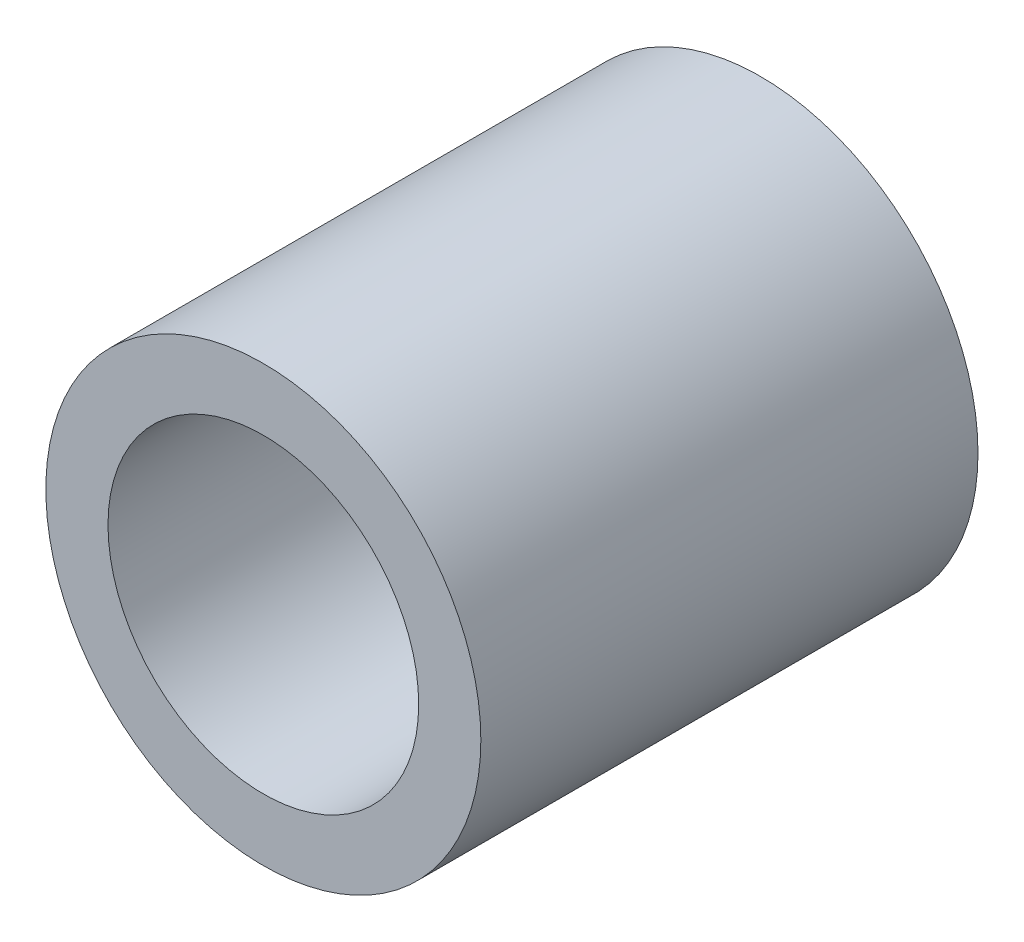
SolidWorks part; units mm, degrees
ref_plane "Front Plane" through (0, 0, 0) normal (1, 0, 0) x (0, 1, 0)
ref_plane "Top Plane" through (0, 0, 0) normal (0, 0, 1) x (0, 1, 0)
ref_plane "Right Plane" through (0, 0, 0) normal (0, 1, 0) x (-1, 0, 0)
sketch "Sketch1" plane through (0, 0, 0) normal (0, 0, 1) x (0, 1, 0)
  circle A0 centre (0, 0) radius 7.9375
  circle A1 centre (0, 0) radius 11.1125
  dimension "D1" = 15.875
  dimension "D2" = 3.175
extrude "Boss-Extrude1" add sketch "Sketch1" along normal blind 25.4
